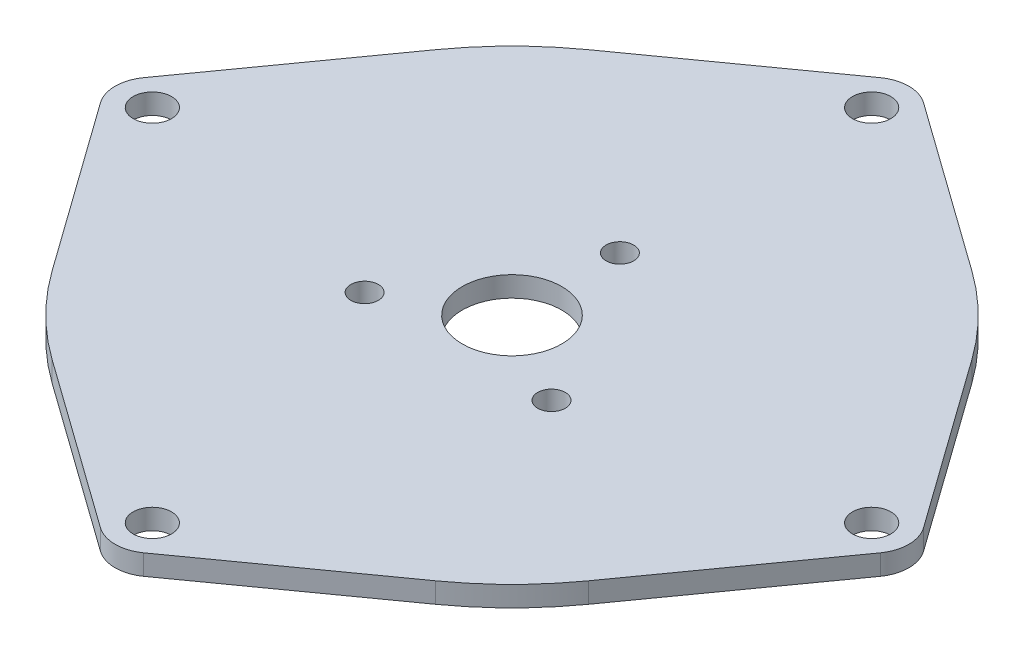
SolidWorks part; units mm, degrees
other "motor_mount" parameters "D1"=97.7653, "D2"=14.7748, "D5"=1.5153, "D6"=1.2729, "D7"=2.6145, "D8"=27.5115, "D9"=27.5368, "D10"=3, "D11"=7.957, "D12"=2, "D14"=6.8142, "D15"=5.6048, "D3"=9, "D4"=4.1559, "D13"=13.0555
material "6061-T6 (SS)"
ref_plane "Front Plane" through (0, 0, 0) normal (0, 0, 1) x (1, 0, 0)
ref_plane "Top Plane" through (0, 0, 0) normal (0, 1, 0) x (1, 0, 0)
ref_plane "Right Plane" through (0, 0, 0) normal (1, 0, 0) x (0, 0, -1)
sketch "Sketch1" plane through (0, 0, 0) normal (0, 1, 0) x (1, 0, 0)
  line L0 (0, 0) -> (0, 9) construction
  line L1 (0, 0) -> (7.7942, -4.5) construction
  line L2 (0, 0) -> (-7.7942, -4.5) construction
  line L3 (15.9994, -22.3667) -> (1.8036, -32.5213)
  line L4 (0, 0) -> (30, 0) construction
  line L5 (-1.8036, -32.5213) -> (-15.9994, -22.3667)
  line L6 (-22.3667, -15.9994) -> (-32.5213, -1.8036)
  line L7 (22.3667, 15.9994) -> (32.5213, 1.8036)
  line L8 (32.5213, -1.8036) -> (22.3667, -15.9994)
  line L9 (-32.5213, 1.8036) -> (-22.3667, 15.9994)
  line L10 (-15.9994, 22.3667) -> (-1.8036, 32.5213)
  line L11 (1.8036, 32.5213) -> (15.9994, 22.3667)
  line L12 (0, 0) -> (22.3667, -15.9994) construction
  circle A0 centre (0, 0) radius 27.5 construction
  circle A1 centre (0, 0) radius 9 construction
  circle A2 centre (0, 9) radius 1.15
  circle A3 centre (7.7942, -4.5) radius 1.15
  circle A4 centre (-7.7942, -4.5) radius 1.15
  circle A8 centre (30, 0) radius 1.6
  circle A9 centre (0, 0) radius 4.15
  arc A11 (32.5213, -1.8036) -> (32.5213, 1.8036) centre (30, 0) ccw
  circle A12 centre (0, 0) radius 27.5
  circle A13 centre (0, -30) radius 1.6
  arc A14 (-1.8036, -32.5213) -> (1.8036, -32.5213) centre (0, -30) ccw
  circle A15 centre (-30, 0) radius 1.6
  arc A16 (-32.5213, 1.8036) -> (-32.5213, -1.8036) centre (-30, 0) ccw
  circle A17 centre (0, 30) radius 1.6
  arc A18 (1.8036, 32.5213) -> (-1.8036, 32.5213) centre (0, 30) ccw
  dimension "D1" = 55
  dimension "D2" = 18
  dimension "D7" = 2.3
  dimension "D11" = 8.3
  dimension "D12" = 3.2
  dimension "D3" = 120
  dimension "D4" = 120
  dimension "D13" = 30
  dimension "D15" = 1.5
  dimension "D6" = 27.5
  dimension "D8" = 35.577
  dimension "D5" = 4
extrude "Boss-Extrude2" add sketch "Sketch1" along normal blind 1.7
equation "\"Hwidth\"= 30"
equation "\"D13@Sketch1\"=\"Hwidth\""
equation "\"Mdia\"=2.3"
equation "\"D7@Sketch1\"=\"Mdia\""
equation "\"Shaft\"=8.3"
equation "\"D11@Sketch1\"=\"Shaft\""
equation "\"Mounthole\"=3.2"
equation "\"D12@Sketch1\"=\"Mounthole\""
equation "\"MainDia\"=55"
equation "\"D1@Sketch1\"=\"MainDia\""
